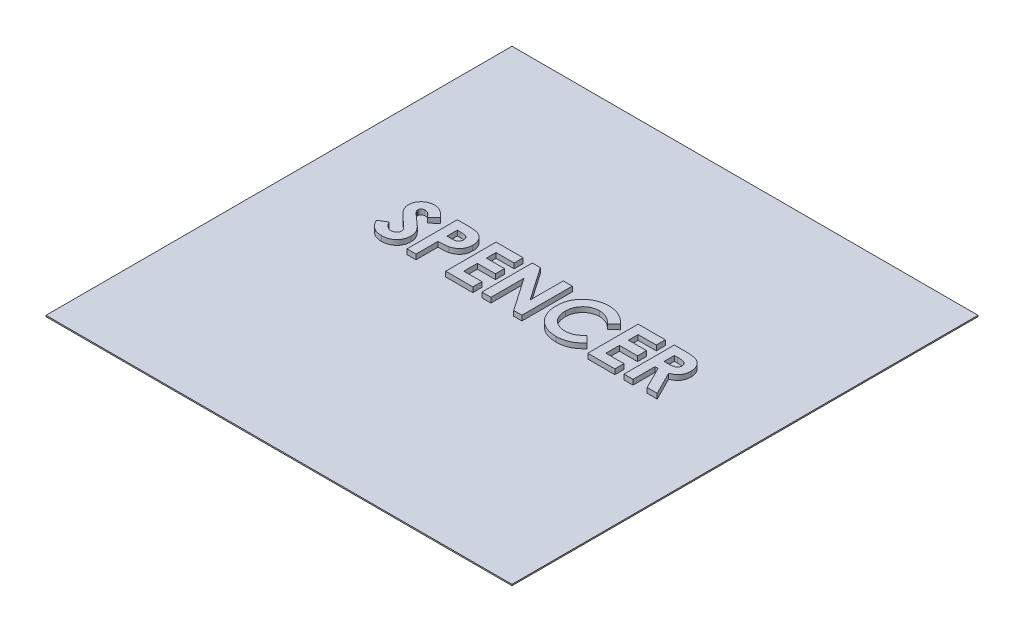
SolidWorks part; units mm, degrees
material "AISI 316 Annealed Stainless Steel Bar (SS)"
ref_plane "Front Plane" through (0, 0, 0) normal (0, 0, 1) x (1, 0, 0)
ref_plane "Top Plane" through (0, 0, 0) normal (0, 1, 0) x (1, 0, 0)
ref_plane "Right Plane" through (0, 0, 0) normal (1, 0, 0) x (0, 0, -1)
sketch "Sketch1" plane through (0, 0, 0) normal (0, 1, 0) x (1, 0, 0)
  line L1 (925, 925) -> (-925, 925)
  line L2 (925, 925) -> (925, -925)
  line L3 (925, -925) -> (-925, -925)
  line L4 (-925, 925) -> (-925, -925)
  line L5 (925, 925) -> (-925, -925) construction
  line L6 (925, -925) -> (-925, 925) construction
  point P0 (0, 0)
  dimension "D1" = 1850
extrude "Boss-Extrude1" add sketch "Sketch1" along normal blind 5
sketch "Sketch2" plane through (0, 5, 0) normal (0, 1, 0) x (1, 0, 0)
  text T0 "SPENCER" font "Century Gothic" height 200
  point P1 (-583.7222, 36.8958)
  point P2 (0, 0)
extrude "Boss-Extrude2" add sketch "Sketch2" along normal blind 20
